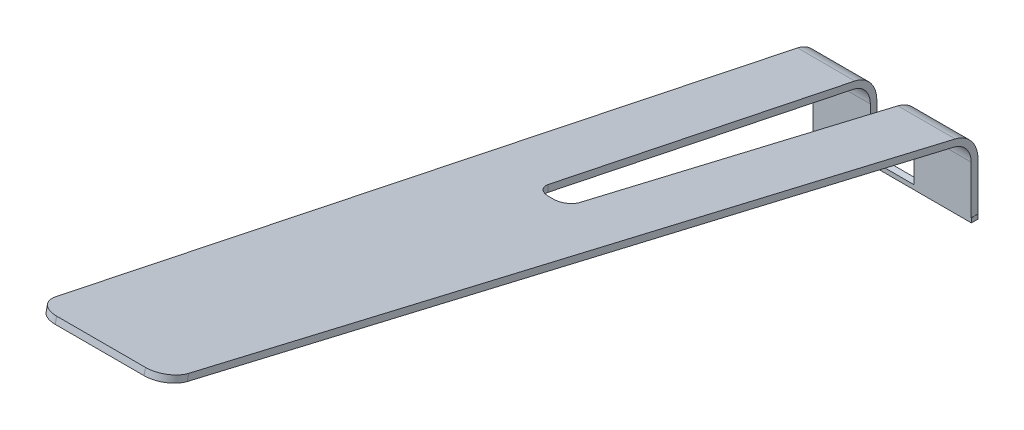
SolidWorks part; units mm, degrees
ref_plane "Спереди" through (0, 0, 0) normal (0, 0, 1) x (1, 0, 0)
ref_plane "Сверху" through (0, 0, 0) normal (0, 1, 0) x (1, 0, 0)
ref_plane "Справа" through (0, 0, 0) normal (1, 0, 0) x (0, 0, -1)
ref_plane "Плоскость4" through (2.85, 0, 0) normal (1, 0, 0) x (0, 0, -1)
sketch "Эскиз1" plane through (2.85, 0, 0) normal (1, 0, 0) x (0, 0, -1)
  line L0 (5.55, 4.85) -> (5.55, 6.0428)
  line L1 (5.1586, 6.5309) -> (-12.45, 10.45)
  line L2 (5.3, 4.85) -> (5.8, 4.85) construction
  line L7 (5.8, 4.95) -> (5.3, 4.95) construction
  arc A0 (5.55, 6.0428) -> (5.1586, 6.5309) centre (5.05, 6.0428) ccw
  point P8 (5.55, 4.95)
  dimension "D3" = 0.5
  dimension "D1" = 18
  dimension "D2" = 12
extrude "Lever" add sketch "Эскиз1" along normal blind 1.8 and the other way blind 1.8 thin
sketch "Эскиз2" plane through (0, 4.95, 0) normal (0, 1, 0) x (1, 0, 0)
  line L0 (1.35, -12.45) -> (4.35, -12.45) construction
  line L1 (2.85, -3.3) -> (2.85, 3.3) construction
  line L2 (4.65, 5.8) -> (1.05, 5.8) construction
  line L4 (1.05, 5.8) -> (1.35, -12.45)
  line L6 (1.05, 5.8) -> (1.05, -12.45)
  line L7 (1.05, -12.45) -> (1.35, -12.45)
  line L8 (2.85, 9.1801) -> (2.85, -8.353) construction
  line L10 (4.65, 5.8) -> (4.65, -12.45)
  line L11 (4.65, 5.8) -> (4.35, -12.45)
  line L12 (4.65, -12.45) -> (4.35, -12.45)
  line L13 (2.35, 5.8) -> (3.35, 5.8)
  line L15 (2.7944, -2.2) -> (2.9056, -2.2)
  line L16 (2.4945, -1.9056) -> (2.35, 5.8)
  line L17 (3.2055, -1.9056) -> (3.35, 5.8)
  line L19 (1.05, -12.45) -> (4.65, -12.45) construction
  arc A0 (2.9056, -2.2) -> (3.2055, -1.9056) centre (2.9056, -1.9) ccw
  arc A1 (2.7944, -2.2) -> (2.4945, -1.9056) centre (2.7944, -1.9) cw
  point P5 (2.85, -12.45)
  point P22 (2.85, 5.8)
  point P25 (2.85, -2.2)
  point P27 (3.2, -2.2)
  point P30 (2.5, -2.2)
  dimension "D5" = 0.3
  dimension "D1" = 3
  dimension "D2" = 8
  dimension "D3" = 1
  dimension "D4" = 0.7
extrude "Cut" cut sketch "Эскиз2" along normal through all
fillet "Скругление1" radius 0.5 2 edges at (4.3503, 10.5232, 12.4337) (1.3497, 10.5232, 12.4337)
